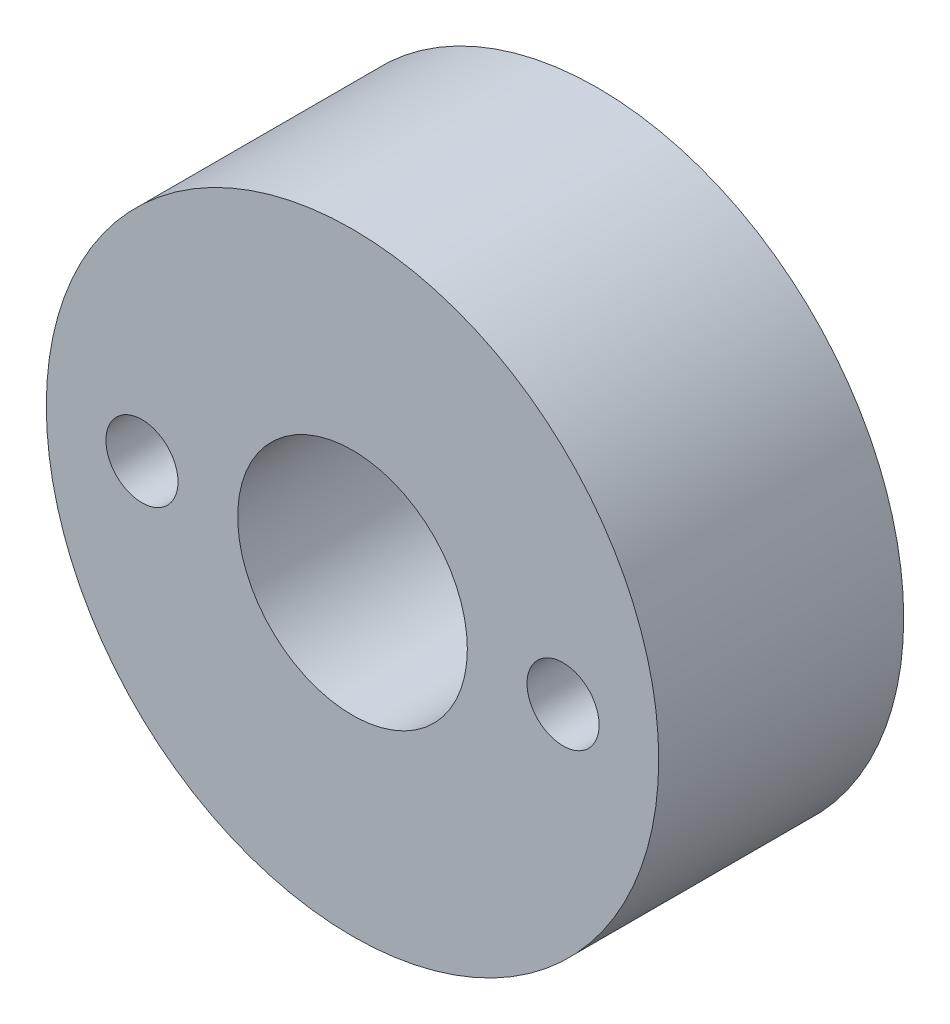
SolidWorks part; units mm, degrees
ref_plane "Front Plane" through (0, 0, 0) normal (0, 0, 1) x (1, 0, 0)
ref_plane "Top Plane" through (0, 0, 0) normal (0, 1, 0) x (1, 0, 0)
ref_plane "Right Plane" through (0, 0, 0) normal (1, 0, 0) x (0, 0, -1)
sketch "Sketch1" plane through (0, 0, 0) normal (0, 0, 1) x (1, 0, 0)
  circle A0 centre (0, 0) radius 12.7
  circle A1 centre (0, 0) radius 4.7625
  dimension "D1" = 9.525
  dimension "D2" = 25.4
extrude "Boss-Extrude1" add sketch "Sketch1" along normal mid plane 10.16
sketch "Sketch2" plane through (0, 0, 5.08) normal (0, 0, 1) x (1, 0, 0)
  line L0 (-7.0232, 0) -> (6.0647, 0)
  circle A0 centre (-8.7325, 0) radius 1.4948
  circle A1 centre (8.7325, 0) radius 1.4948
  dimension "D1" = 2.9896
  dimension "D2" = 2.9896
  dimension "D3" = 0
  dimension "D4" = 0
  dimension "D5" = 8.7325
  dimension "D6" = 8.7325
extrude "Cut-Extrude1" cut sketch "Sketch2" against normal blind 10.16 contours A1 | A0
